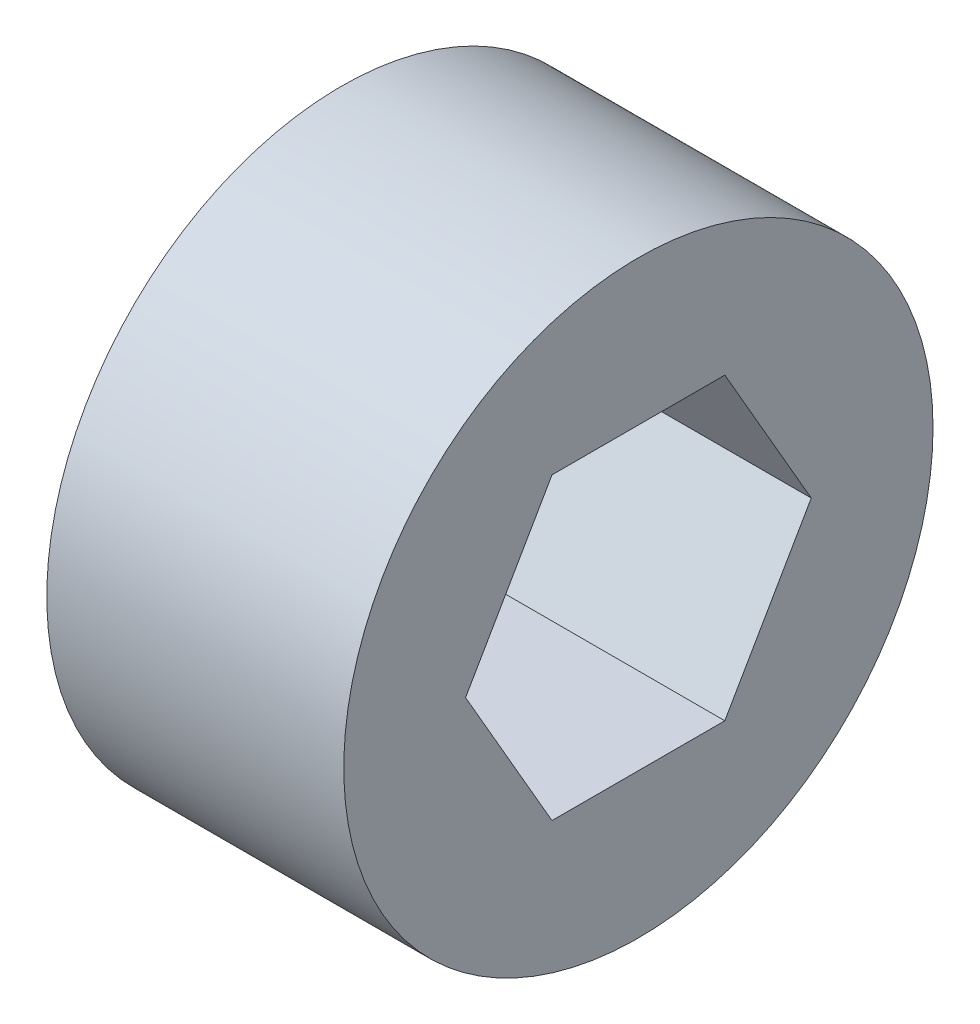
SolidWorks part; units mm, degrees
ref_plane "Alzado" through (0, 0, 0) normal (0, 0, 1) x (1, 0, 0)
ref_plane "Planta" through (0, 0, 0) normal (0, 1, 0) x (1, 0, 0)
ref_plane "Vista lateral" through (0, 0, 0) normal (1, 0, 0) x (0, 0, -1)
sketch "Croquis1" plane through (0, 0, 0) normal (1, 0, 0) x (0, 0, -1)
  line L1 (7.3323, 0) -> (3.6662, 6.35)
  line L2 (3.6662, 6.35) -> (-3.6662, 6.35)
  line L3 (-3.6662, 6.35) -> (-7.3323, 0)
  line L4 (-7.3323, 0) -> (-3.6662, -6.35)
  line L5 (-3.6662, -6.35) -> (3.6662, -6.35)
  line L6 (3.6662, -6.35) -> (7.3323, 0)
  circle A0 centre (0, 0) radius 12.5
  circle A1 centre (0, 0) radius 6.35 construction
  dimension "D2" = 25
  dimension "D1" = 12.7
extrude "Saliente-Extruir1" add sketch "Croquis1" along normal blind 12.6
